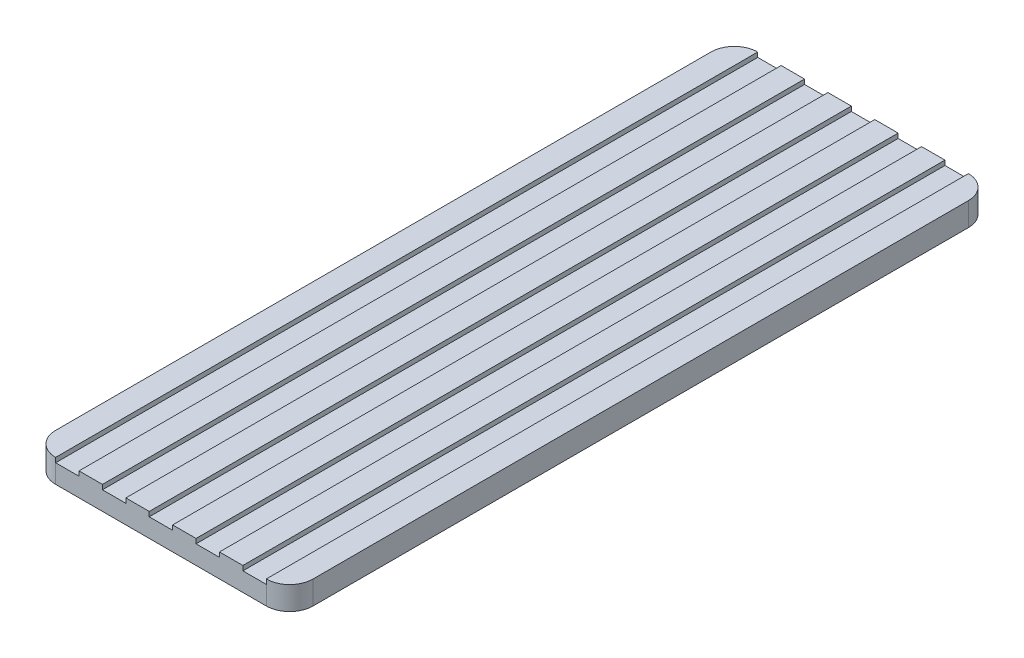
SolidWorks part; units mm, degrees
ref_plane "Front Plane" through (0, 0, 0) normal (0, 0, 1) x (1, 0, 0)
ref_plane "Top Plane" through (0, 0, 0) normal (0, 1, 0) x (1, 0, 0)
ref_plane "Right Plane" through (0, 0, 0) normal (1, 0, 0) x (0, 0, -1)
sketch "Sketch2" plane through (0, 0, 0) normal (0, 1, 0) x (1, 0, 0)
  line L1 (-27.5, -75) -> (27.5, -75)
  line L2 (-27.5, -75) -> (-27.5, 75)
  line L3 (-27.5, 75) -> (27.5, 75)
  line L4 (27.5, -75) -> (27.5, 75)
  line L5 (-27.5, -75) -> (27.5, 75) construction
  line L6 (-27.5, 75) -> (27.5, -75) construction
  point P0 (0, 0)
  dimension "D1" = 150
  dimension "D2" = 55
extrude "Boss-Extrude1" add sketch "Sketch2" along normal blind 5
fillet "Fillet1" radius 5 4 edges at (-27.5, 2.5, 75) (-27.5, 2.5, -75) (27.5, 2.5, -75) (27.5, 2.5, 75)
sketch "Sketch4" plane through (0, 0, 75) normal (0, 0, 1) x (1, 0, 0)
  line L0 (-22.5, 5) -> (22.5, 5) construction
  line L1 (-22.5, 5) -> (-17.5, 5)
  line L2 (-22.5, 5) -> (-22.5, 4)
  line L3 (-22.5, 4) -> (-17.5, 4)
  line L4 (-17.5, 5) -> (-17.5, 4)
  line L5 (-27.5, 0) -> (-27.5, 5) construction
  dimension "D1" = 1
  dimension "D2" = 5
  dimension "D3" = 5
extrude "Cut-Extrude1" cut sketch "Sketch4" against normal through all
pattern_linear "LPattern1" count 5 spacing 10 along (1, 0, 0) of "Cut-Extrude1"
